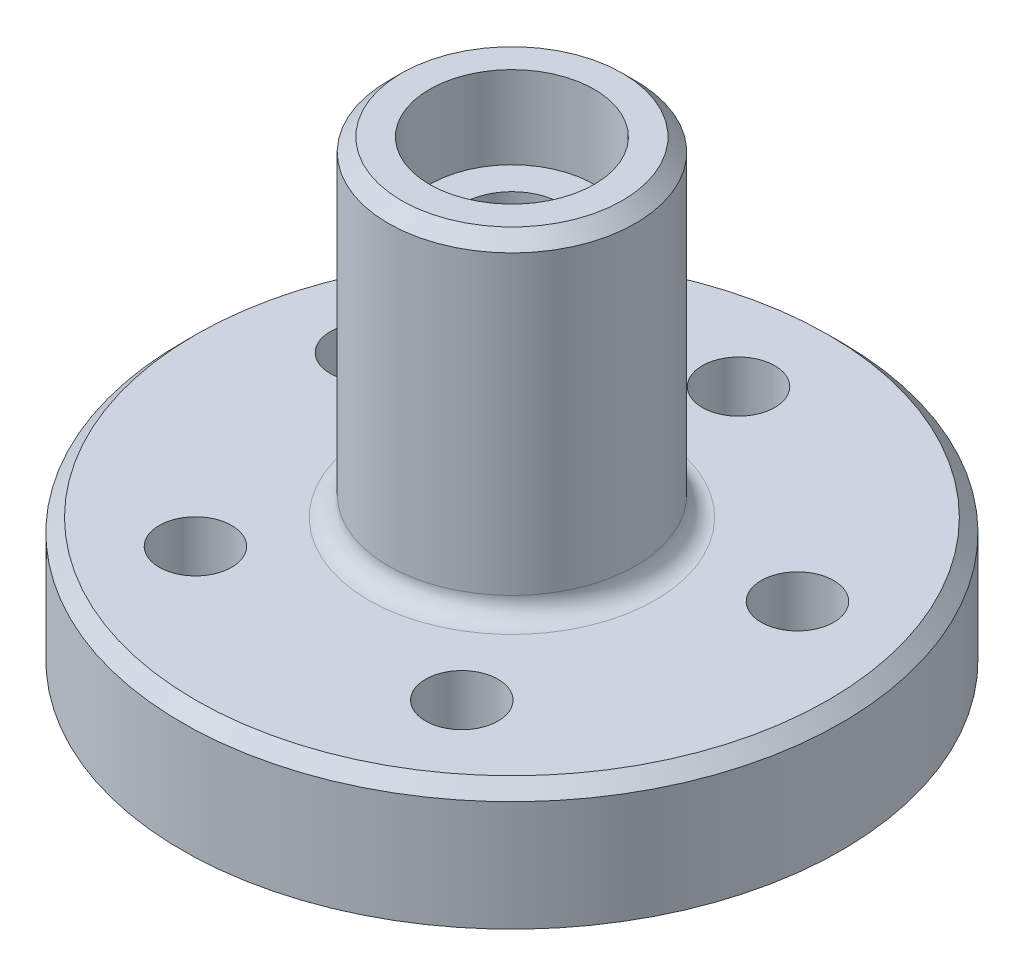
SolidWorks part; units mm, degrees
ref_plane "Front Plane" through (0, 0, 0) normal (0, 0, 1) x (1, 0, 0)
ref_plane "Top Plane" through (0, 0, 0) normal (0, 1, 0) x (1, 0, 0)
ref_plane "Right Plane" through (0, 0, 0) normal (1, 0, 0) x (0, 0, -1)
sketch "Sketch1" plane through (0, 0, 0) normal (0, 1, 0) x (1, 0, 0)
  circle A0 centre (0, 0) radius 50.8
  dimension "D1" = 101.6
extrude "Boss-Extrude1" add sketch "Sketch1" along normal blind 19.05
chamfer "Chamfer1" distance 2.032 angle 45 1 edges at (0, 19.05, 50.8)
sketch "Sketch2" plane through (0, 19.05, 0) normal (0, 1, 0) x (1, 0, 0)
  circle A0 centre (0, 0) radius 34.925 construction
  circle A1 centre (0, 34.925) radius 5.588
  circle A2 centre (33.2156, 10.7924) radius 5.588
  circle A3 centre (0, 0) radius 34.925 construction
  circle A4 centre (20.5284, -28.2549) radius 5.588
  circle A5 centre (0, 0) radius 34.925 construction
  circle A6 centre (-20.5284, -28.2549) radius 5.588
  circle A7 centre (0, 0) radius 34.925 construction
  circle A8 centre (-33.2156, 10.7924) radius 5.588
  circle A9 centre (0, 0) radius 34.925 construction
  point P20 (0, 0)
  dimension "D1" = 69.85
  dimension "D2" = 11.176
  dimension "D3" = 5
extrude "Cut-Extrude2" cut sketch "Sketch2" against normal through all
sketch "Sketch4" plane through (0, 19.05, 0) normal (0, 1, 0) x (1, 0, 0)
  circle A0 centre (0, 0) radius 19.05
  dimension "D1" = 38.1
extrude "Boss-Extrude2" add sketch "Sketch4" along normal blind 50.8
fillet "Fillet1" radius 3.048 1 edges at (0, 19.05, 19.05)
chamfer "Chamfer2" distance 2.032 angle 45 1 edges at (0, 69.85, 19.05)
sketch "Sketch5" plane through (0, 69.85, 0) normal (0, 1, 0) x (1, 0, 0)
  circle A0 centre (0, 0) radius 12.7
  dimension "D1" = 25.4
extrude "Cut-Extrude3" cut sketch "Sketch5" against normal blind 12.7
sketch "Sketch6" plane through (0, 57.15, 0) normal (0, 1, 0) x (1, 0, 0)
  circle A0 centre (0, 0) radius 7.62
  dimension "D1" = 15.24
extrude "Cut-Extrude4" cut sketch "Sketch6" against normal through all
